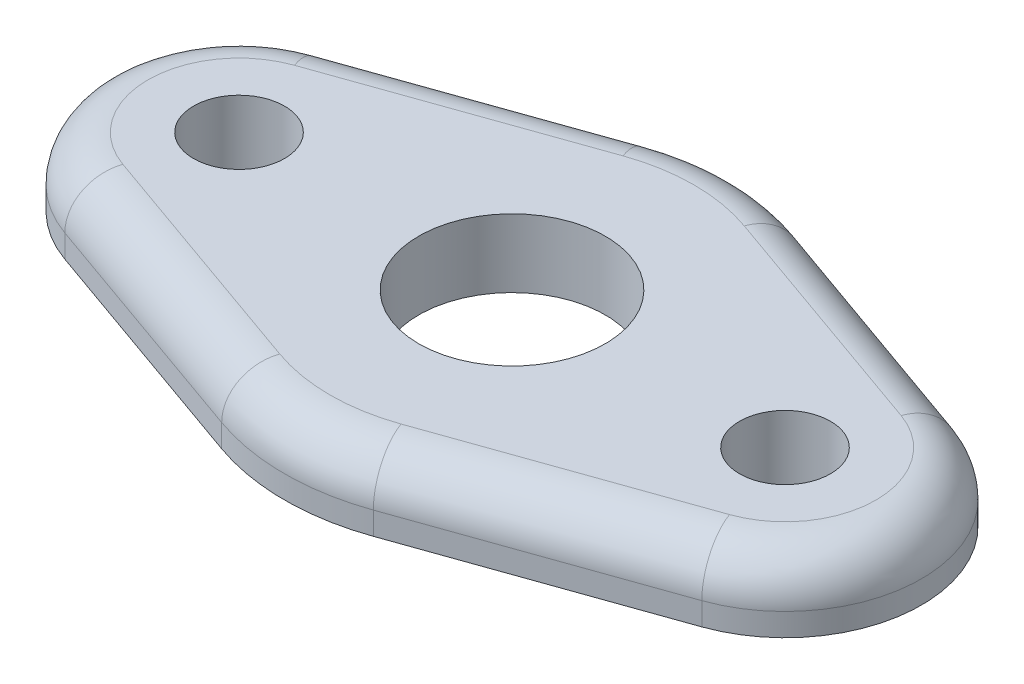
SolidWorks part; units mm, degrees
ref_plane "Front Plane" through (0, 0, 0) normal (0, 0, 1) x (1, 0, 0)
ref_plane "Top Plane" through (0, 0, 0) normal (0, 1, 0) x (1, 0, 0)
ref_plane "Right Plane" through (0, 0, 0) normal (1, 0, 0) x (0, 0, -1)
sketch "Sketch1" plane through (0, 0, 0) normal (0, 1, 0) x (1, 0, 0)
  line L0 (-14, 5.6569) -> (-3.3333, 9.4281)
  line L1 (3.3333, 9.4281) -> (14, 5.6569)
  line L3 (3.3333, -9.4281) -> (14, -5.6569)
  line L4 (-14, -5.6569) -> (-3.3333, -9.4281)
  circle A0 centre (0, 0) radius 4.1
  circle A1 centre (-12, 0) radius 2
  circle A2 centre (12, 0) radius 2
  arc A3 (-3.3333, -9.4281) -> (3.3333, -9.4281) centre (0, 0) ccw
  arc A4 (-14, 5.6569) -> (-14, -5.6569) centre (-12, 0) ccw
  arc A5 (14, -5.6569) -> (14, 5.6569) centre (12, 0) ccw
  arc A7 (3.3333, 9.4281) -> (-3.3333, 9.4281) centre (0, 0) ccw
  dimension "D1" = 8.2
  dimension "D2" = 4
  dimension "D5" = 20
  dimension "D6" = 12
  dimension "D7" = 12
  dimension "D3" = 12
  dimension "D4" = 12
extrude "Boss-Extrude1" add sketch "Sketch1" along normal blind 3
fillet "Fillet1" radius 2 8 edges at (0, 3, 10) (-8.6667, 3, 7.5425) (-18, 3, 0) (-8.6667, 3, -7.5425) (0, 3, -10) (8.6667, 3, -7.5425) (18, 3, 0) (8.6667, 3, 7.5425)
